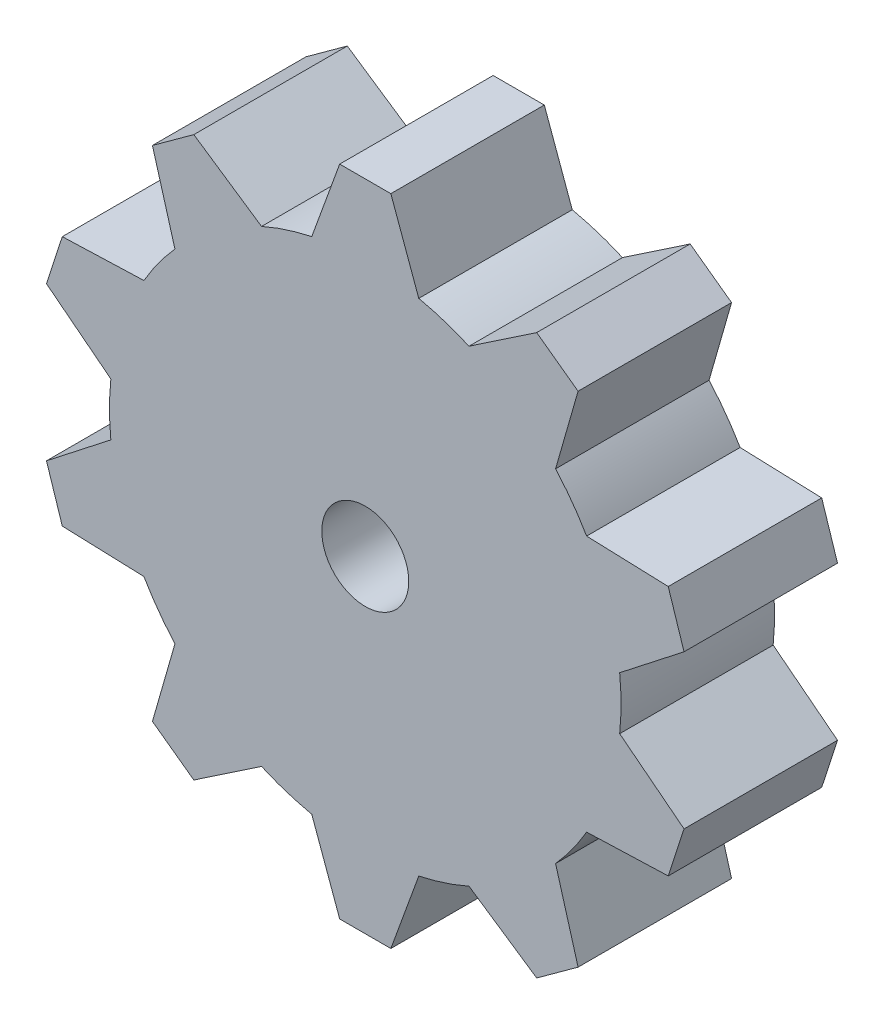
SolidWorks part; units mm, degrees
ref_plane "Front Plane" through (0, 0, 0) normal (0, 0, 1) x (1, 0, 0)
ref_plane "Top Plane" through (0, 0, 0) normal (0, 1, 0) x (1, 0, 0)
ref_plane "Right Plane" through (0, 0, 0) normal (1, 0, 0) x (0, 0, -1)
sketch "Sketch1" plane through (0, 0, 0) normal (0, 0, 1) x (1, 0, 0)
  line L27 (-1.046, 4.8894) -> (-0.5, 6.3894)
  line L28 (-0.5, 6.3894) -> (0.5, 6.3894)
  line L29 (0.5, 6.3894) -> (1.046, 4.8894)
  line L30 (2.0277, 4.5704) -> (3.3511, 5.463)
  line L31 (3.3511, 5.463) -> (4.1601, 4.8752)
  line L32 (4.1601, 4.8752) -> (3.7201, 3.3408)
  line L33 (4.3269, 2.5057) -> (5.9221, 2.45)
  line L34 (5.9221, 2.45) -> (6.2312, 1.4989)
  line L35 (6.2312, 1.4989) -> (4.9733, 0.5161)
  line L36 (4.9733, -0.5161) -> (6.2312, -1.4989)
  line L37 (6.2312, -1.4989) -> (5.9221, -2.45)
  line L38 (5.9221, -2.45) -> (4.3269, -2.5057)
  line L39 (3.7201, -3.3408) -> (4.1601, -4.8752)
  line L40 (4.1601, -4.8752) -> (3.3511, -5.463)
  line L41 (3.3511, -5.463) -> (2.0277, -4.5704)
  line L42 (1.046, -4.8894) -> (0.5, -6.3894)
  line L43 (0.5, -6.3894) -> (-0.5, -6.3894)
  line L44 (-0.5, -6.3894) -> (-1.046, -4.8894)
  line L45 (-2.0277, -4.5704) -> (-3.3511, -5.463)
  line L46 (-3.3511, -5.463) -> (-4.1601, -4.8752)
  line L47 (-4.1601, -4.8752) -> (-3.7201, -3.3408)
  line L48 (-4.3269, -2.5057) -> (-5.9221, -2.45)
  line L49 (-5.9221, -2.45) -> (-6.2312, -1.4989)
  line L50 (-6.2312, -1.4989) -> (-4.9733, -0.5161)
  line L51 (-4.9733, 0.5161) -> (-6.2312, 1.4989)
  line L52 (-6.2312, 1.4989) -> (-5.9221, 2.45)
  line L53 (-5.9221, 2.45) -> (-4.3269, 2.5057)
  line L54 (-3.7201, 3.3408) -> (-4.1601, 4.8752)
  line L55 (-4.1601, 4.8752) -> (-3.3511, 5.463)
  line L56 (-3.3511, 5.463) -> (-2.0277, 4.5704)
  circle A1 centre (0, 0) radius 0.85
  arc A10 (-3.7201, 3.3408) -> (-4.3269, 2.5057) centre (0, 0) ccw
  arc A11 (-1.046, 4.8894) -> (-2.0277, 4.5704) centre (0, 0) ccw
  arc A12 (2.0277, 4.5704) -> (1.046, 4.8894) centre (0, 0) ccw
  arc A13 (4.3269, 2.5057) -> (3.7201, 3.3408) centre (0, 0) ccw
  arc A14 (4.9733, -0.5161) -> (4.9733, 0.5161) centre (0, 0) ccw
  arc A15 (1.046, -4.8894) -> (2.0277, -4.5704) centre (0, 0) ccw
  arc A16 (3.7201, -3.3408) -> (4.3269, -2.5057) centre (0, 0) ccw
  arc A17 (-2.0277, -4.5704) -> (-1.046, -4.8894) centre (0, 0) ccw
  arc A18 (-4.3269, -2.5057) -> (-3.7201, -3.3408) centre (0, 0) ccw
  arc A19 (-4.9733, 0.5161) -> (-4.9733, -0.5161) centre (0, 0) ccw
  point P46 (0, 0)
  dimension "D1" = 10
  dimension "D2" = 1
  dimension "D3" = 1.5
  dimension "D4" = 110
  dimension "D5" = 110
extrude "Boss-Extrude1" add sketch "Sketch1" along normal blind 3
